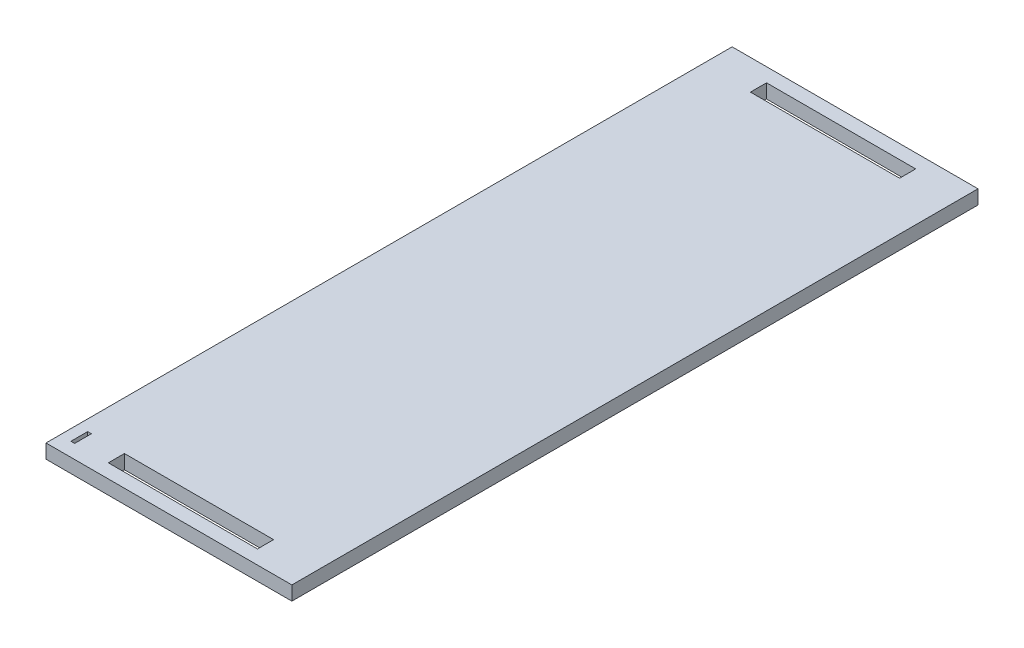
SolidWorks part; units mm, degrees
ref_plane "Front Plane" through (0, 0, 0) normal (0, 0, 1) x (1, 0, 0)
ref_plane "Top Plane" through (0, 0, 0) normal (0, 1, 0) x (1, 0, 0)
ref_plane "Right Plane" through (0, 0, 0) normal (1, 0, 0) x (0, 0, -1)
sketch "Sketch1" plane through (0, 0, 0) normal (0, 1, 0) x (1, 0, 0)
  line L0 (-26.169, 66.4972) -> (26.169, 66.4972) construction
  line L1 (26.169, -73.025) -> (-26.169, -73.025)
  line L2 (26.169, -73.025) -> (26.169, 73.025)
  line L3 (26.169, 73.025) -> (-26.169, 73.025)
  line L4 (-26.169, -73.025) -> (-26.169, 73.025)
  line L5 (26.169, -73.025) -> (-26.169, 73.025) construction
  line L6 (26.169, 73.025) -> (-26.169, -73.025) construction
  line L7 (-26.169, -66.4972) -> (26.169, -66.4972) construction
  line L8 (-26.169, 66.4972) -> (-26.169, -66.4972) construction
  line L9 (26.169, 66.4972) -> (26.169, -66.4972) construction
  line L10 (0, 66.6242) -> (0, -66.6242) construction
  line L11 (-15.875, 70.0532) -> (15.875, 70.0532)
  line L12 (-15.875, 70.0532) -> (-15.875, 66.6242)
  line L13 (-15.875, 66.6242) -> (15.875, 66.6242)
  line L14 (15.875, 70.0532) -> (15.875, 66.6242)
  line L15 (-15.875, -66.6242) -> (15.875, -66.6242)
  line L16 (-15.875, -66.6242) -> (-15.875, -70.0532)
  line L17 (-15.875, -70.0532) -> (15.875, -70.0532)
  line L18 (15.875, -66.6242) -> (15.875, -70.0532)
  line L19 (-26.169, -70.0532) -> (26.169, -70.0532) construction
  line L21 (-23.8297, -66.4972) -> (-23.036, -66.4972)
  line L22 (-23.8297, -66.4972) -> (-23.8297, -70.0532)
  line L23 (-23.8297, -70.0532) -> (-23.036, -70.0532)
  line L24 (-23.036, -66.4972) -> (-23.036, -70.0532)
  point P0 (0, 0)
  point P10 (26.169, 0)
  point P11 (26.169, 0)
  point P16 (0, 66.6242)
  point P17 (0, 0)
  dimension "D1" = 52.338
  dimension "D2" = 146.05
  dimension "D3" = 132.9944
  dimension "D4" = 3.429
  dimension "D5" = 31.75
  dimension "D6" = 0.254
  dimension "D7" = 0.7937
extrude "Boss-Extrude1" add sketch "Sketch1" along normal blind 2.9972
